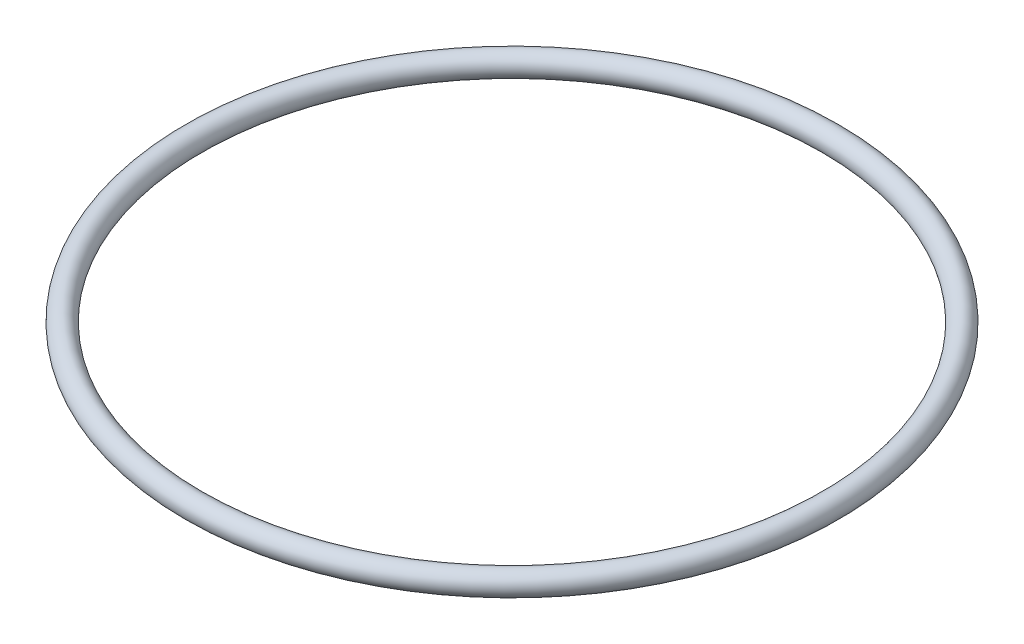
SolidWorks part; units mm, degrees
ref_plane "Спереди" through (0, 0, 0) normal (0, 0, 1) x (1, 0, 0)
ref_plane "Сверху" through (0, 0, 0) normal (0, 1, 0) x (1, 0, 0)
ref_plane "Справа" through (0, 0, 0) normal (1, 0, 0) x (0, 0, -1)
sketch "Эскиз1" plane through (0, 0, 0) normal (0, 0, 1) x (1, 0, 0)
  line L0 (-10.3159, 0) -> (10.7899, 0) construction
  line L1 (0, 8.2838) -> (0, -15.392) construction
  circle A0 centre (-34.75, 0) radius 1.25
  dimension "D1" = 2.5
  dimension "D2" = 69.5
revolve "Повернуть1" add sketch "Эскиз1" angle 360 about L1
